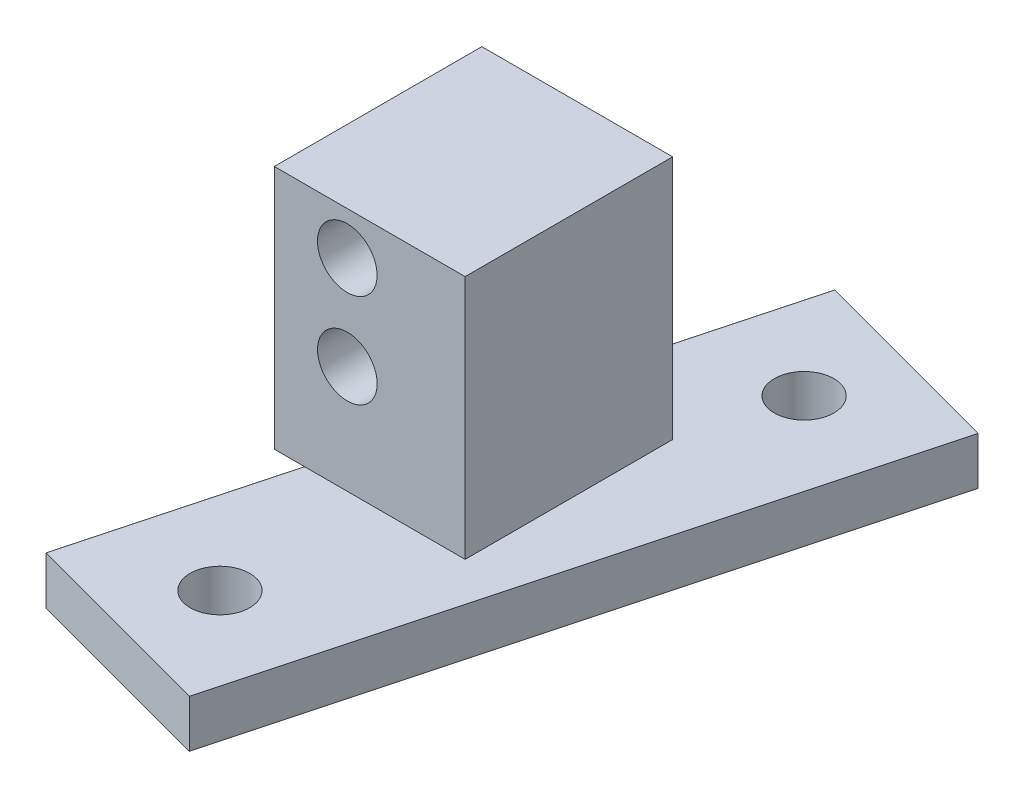
SolidWorks part; units mm, degrees
ref_plane "Front Plane" through (0, 0, 0) normal (0, 0, 1) x (1, 0, 0)
ref_plane "Top Plane" through (0, 0, 0) normal (0, 1, 0) x (1, 0, 0)
ref_plane "Right Plane" through (0, 0, 0) normal (1, 0, 0) x (0, 0, -1)
sketch "Sketch1" plane through (0, 0, 0) normal (0, 0, 1) x (1, 0, 0)
  line L0 (-111.8199, 128.5717) -> (-91.4999, 128.5717)
  line L1 (-135.8002, 128.5591) -> (-97.86, 128.5791) construction
  line L2 (-91.4999, 128.5717) -> (-91.4999, 102.49)
  line L3 (-91.4999, 102.49) -> (-111.8199, 102.49)
  line L4 (-111.8199, 102.49) -> (-111.8199, 128.5717)
  line L5 (-113.109, 106.2952) -> (-104.0412, 106.3) construction
  line L6 (-113.109, 106.2952) -> (-104.0412, 106.3)
  arc A0 (-99.2776, 107.9535) -> (-97.8499, 109.4275) centre (-104.0452, 114) ccw construction
  arc A1 (-104.0412, 106.3) -> (-99.2776, 107.9535) centre (-104.0452, 114) ccw construction
  arc A2 (-99.2776, 107.9535) -> (-97.8499, 109.4275) centre (-104.0452, 114) ccw
  arc A3 (-104.0412, 106.3) -> (-99.2776, 107.9535) centre (-104.0452, 114) ccw
  circle A4 centre (-104.0452, 114) radius 3.175
  circle A5 centre (-104.0505, 124) radius 3.175
  dimension "D4" = 6.35
  dimension "D5" = 6.35
  dimension "D1" = 3.81
  dimension "D2" = 20.32
  dimension "D3" = 6.35
extrude "Boss-Extrude1" add sketch "Sketch1" along normal up to surface (22.098 mm away)
ref_plane "Plane1" through (0, 102.49, 0) normal (0, 1, 0) x (1, 0, 0)
sketch "Sketch2" plane through (0, 102.49, 0) normal (0, 1, 0) x (1, 0, 0)
  line L0 (-96.6636, 22.4204) -> (-114.4134, -43.8228)
  line L1 (-114.4134, -43.8228) -> (-93.5591, -49.4107)
  line L2 (-93.5591, -49.4107) -> (-75.8093, 16.8325)
  line L3 (-75.8093, 16.8325) -> (-96.6636, 22.4204)
  line L4 (-111.8199, -22.098) -> (-91.4999, -22.098) construction
  circle A0 centre (-101.6854, -38.0296) radius 3.175
  circle A1 centre (-88.5374, 11.0394) radius 3.175
  dimension "D6" = 8.89
  dimension "D10" = 6.35
  dimension "D11" = 6.35
  dimension "D1" = 105
  dimension "D2" = 5.08
  dimension "D3" = 68.58
  dimension "D4" = 21.59
  dimension "D5" = 20.32
  dimension "D7" = 8.89
  dimension "D8" = 10.795
  dimension "D9" = 10.795
extrude "Boss-Extrude2" add sketch "Sketch2" against normal blind 5.08
